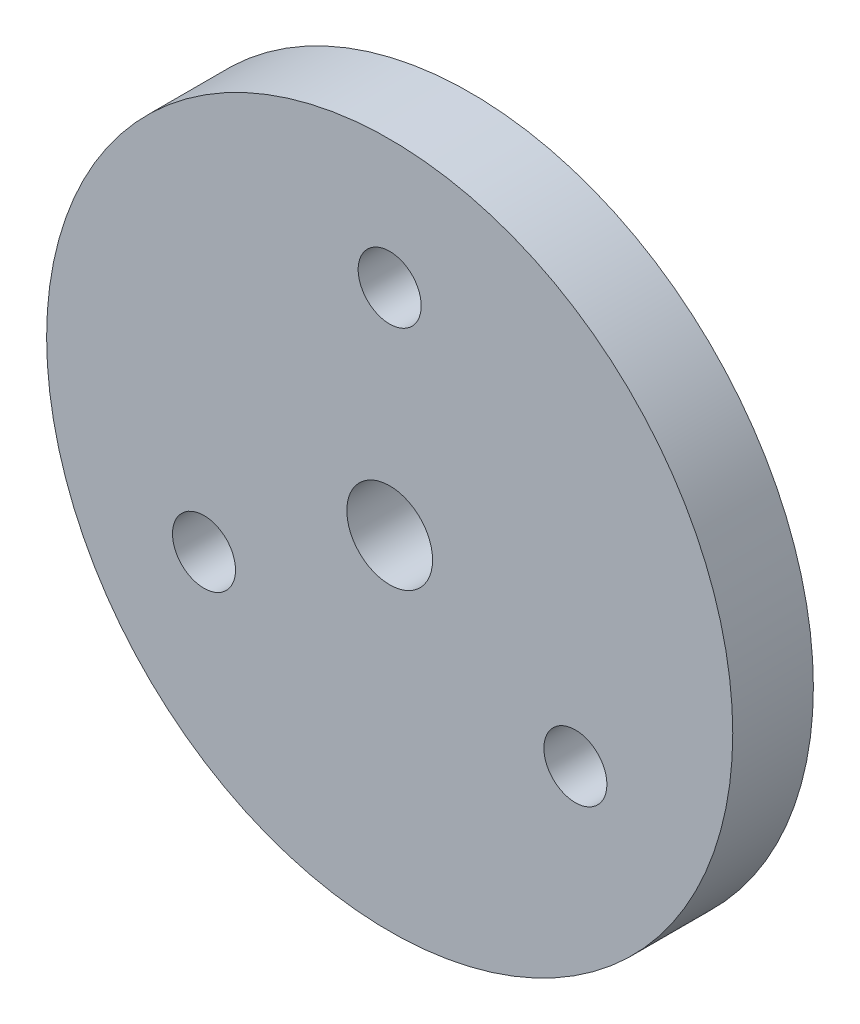
SolidWorks part; units mm, degrees
ref_plane "Front Plane" through (0, 0, 0) normal (0, 0, 1) x (1, 0, 0)
ref_plane "Top Plane" through (0, 0, 0) normal (0, 1, 0) x (1, 0, 0)
ref_plane "Right Plane" through (0, 0, 0) normal (1, 0, 0) x (0, 0, -1)
sketch "Sketch1" plane through (0, 0, 0) normal (0, 0, 1) x (1, 0, 0)
  circle A0 centre (0, 0) radius 50.8
  dimension "D1" = 101.6
extrude "top_plate" add sketch "Sketch1" along normal blind 11.938
sketch "coupling_circle" plane through (0, 0, 11.938) normal (0, 0, 1) x (1, 0, 0)
  circle A0 centre (0, 0) radius 31.75
  dimension "D1" = 63.5
sketch "Sketch2" plane through (0, 0, 11.938) normal (0, 0, 1) x (1, 0, 0)
  circle A0 centre (0, 0) radius 6.35
  dimension "D1" = 12.7
extrude "central_hole" cut sketch "Sketch2" against normal through all
sketch "Sketch3" plane through (0, 0, 11.938) normal (0, 0, 1) x (1, 0, 0)
  circle A0 centre (0, 31.75) radius 4.6663
  circle A1 centre (0, 0) radius 31.75 construction
  dimension "D1" = 9.3326
extrude "ball_hole" cut sketch "Sketch3" against normal blind 11.938
pattern_circular "ball_hole_pattern" count 3 over 360 about axis through (0, 0, 0) along (0, 0, 1) of "ball_hole"
equation "\"plate_diam\"= 4"
equation "\"magnet_thickness\"= 0.125"
equation "\"coupling_diam\"= 2.5"
equation "\"ball_diam\"= .375"
equation "\"dowel_diam\"= 0.25"
equation "\"plate_thickness\"= 0.47"
equation "\"magnet_diam\"=1.26"
equation "\"glue_thickness\"= 0.005"
equation "\"magnet_radial_tol\"= 0.0025"
equation "\"dowel_length\"= .75"
equation "\"dowel_center_to_center\" = 2 * ( sqr ( ( ( ( \"dowel_diam\" + \"ball_diam\" ) / 2 ) ^ 2 ) / 2 ) )"
equation "\"dowel_slot_width\"= \"dowel_center_to_center\" + \"dowel_diam\""
equation "\"dowel_slot_depth\" = \"dowel_diam\" * 0.75"
equation "\"corner_relief_diam\"= 0.25"
equation "\"central_hole_diam\"= 0.5"
equation "\"ball_center_to_slot_bottom\"= ( \"dowel_center_to_center\" / 2 ) + ( \"dowel_diam\" / 2 )"
equation "\"total_coupling_height\"= 1"
equation "\"ball_embed_depth\"= 0.15"
equation "\"ball_hole_diam\"= 2 * sqr ( ( \"ball_diam\" / 2 ) ^ 2 + - ( \"ball_diam\" / 2 - \"ball_embed_depth\" ) ^ 2 )"
equation "\"total_stack_height\"= \"plate_thickness\" - \"dowel_slot_depth\" + \"ball_center_to_slot_bottom\" + ( \"ball_diam\" / 2 ) - \"ball_embed_depth\" + \"plate_thickness\""
equation "\"D1@Sketch1\"=\"plate_diam\""
equation "\"D1@top_plate\" = \"plate_thickness\""
equation "\"D1@Sketch2\"=\"central_hole_diam\""
equation "\"D1@Sketch3\"=\"ball_hole_diam\""
equation "\"D1@coupling_circle\" = \"coupling_diam\""
